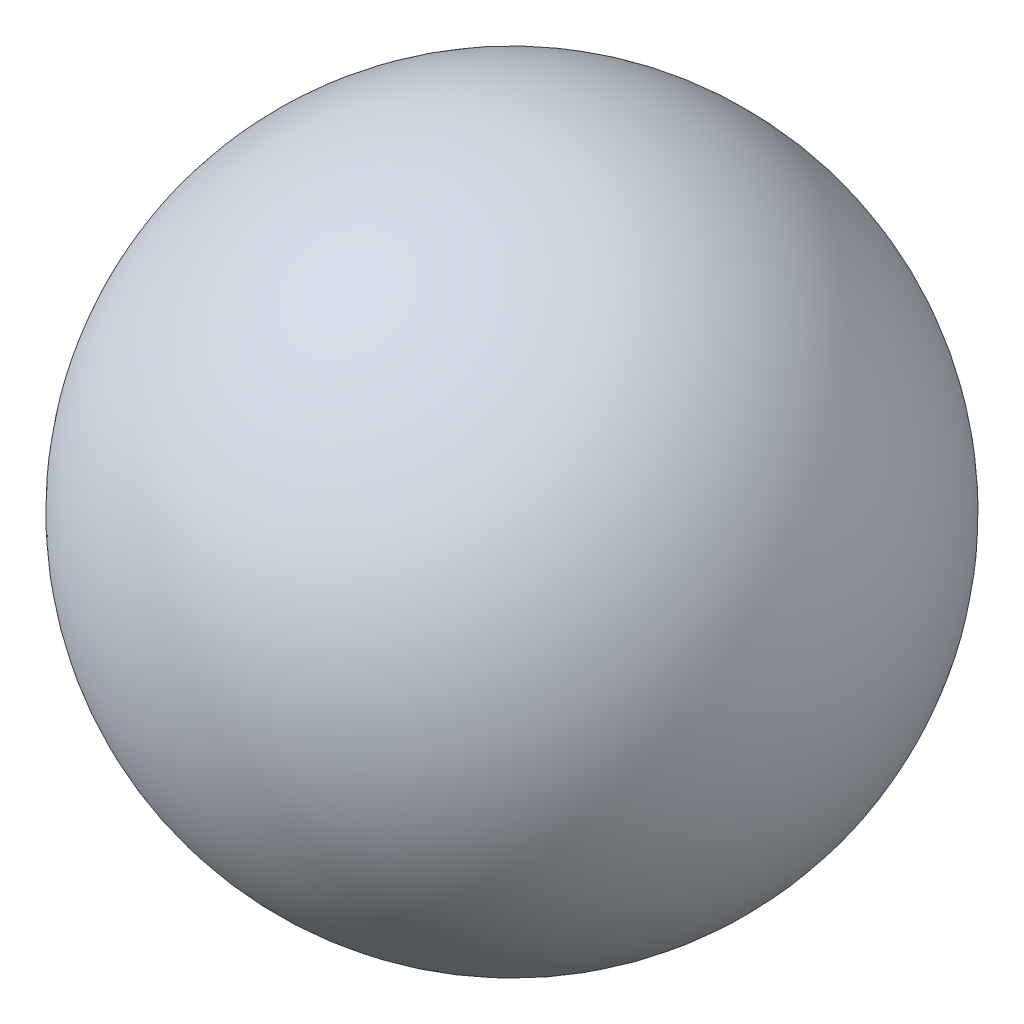
SolidWorks part; units mm, degrees
ref_plane "Piano frontale" through (0, 0, 0) normal (0, 0, 1) x (1, 0, 0)
ref_plane "Piano superiore" through (0, 0, 0) normal (0, 1, 0) x (1, 0, 0)
ref_plane "Piano destro" through (0, 0, 0) normal (1, 0, 0) x (0, 0, -1)
ref_plane "Piano1" through (0, 0, 0) normal (0, 0, 1) x (1, 0, 0)
sketch "Schizzo1" plane through (0, 0, 0) normal (0, 0, 1) x (1, 0, 0)
  line L0 (25.806, 66.275) -> (1.994, 66.275)
  line L1 (25.806, 66.275) -> (1.994, 66.275) construction
  arc A0 (1.994, 66.275) -> (25.806, 66.275) centre (13.9, 66.275) cw
revolve "Rivoluzione1" add sketch "Schizzo1" angle 360 about L1
